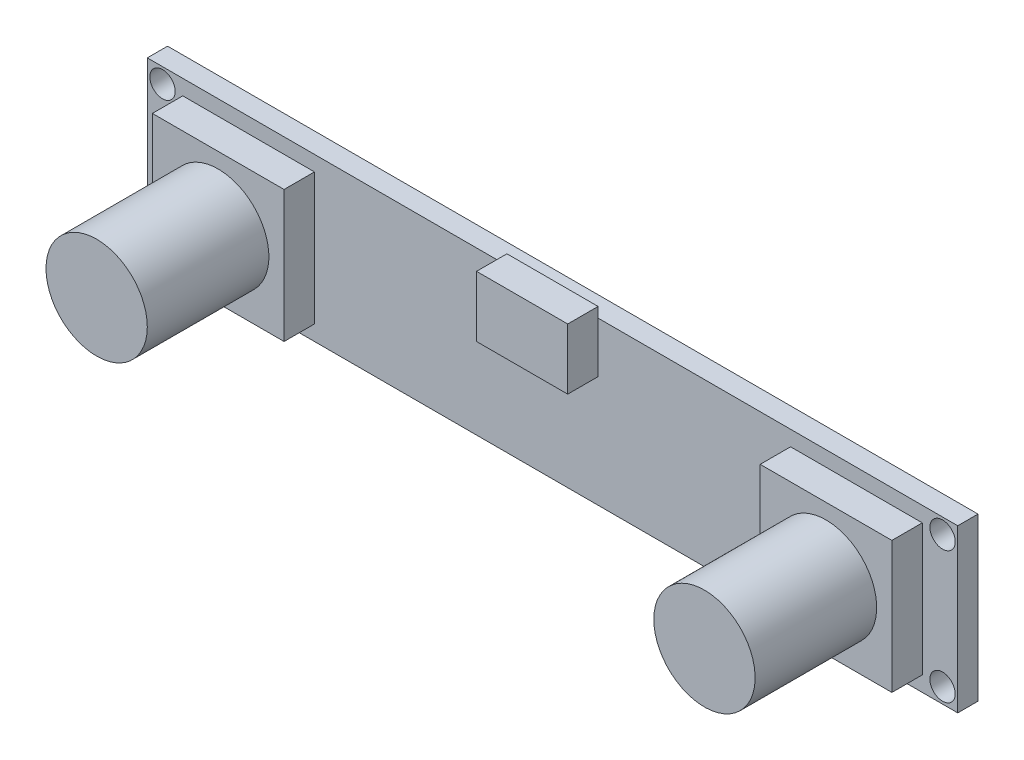
SolidWorks part; units mm, degrees
ref_plane "Спереди" through (0, 0, 0) normal (0, 0, 1) x (1, 0, 0)
ref_plane "Сверху" through (0, 0, 0) normal (0, 1, 0) x (1, 0, 0)
ref_plane "Справа" through (0, 0, 0) normal (1, 0, 0) x (0, 0, -1)
sketch "Эскиз1" plane through (0, 0, 0) normal (0, 0, 1) x (1, 0, 0)
  line L1 (-40, -8) -> (40, -8)
  line L2 (-40, -8) -> (-40, 8)
  line L3 (-40, 8) -> (40, 8)
  line L4 (40, -8) -> (40, 8)
  line L5 (-40, -8) -> (40, 8) construction
  line L6 (-40, 8) -> (40, -8) construction
  point P0 (0, 0)
  dimension "D1" = 80
  dimension "D2" = 16
extrude "тело" add sketch "Эскиз1" along normal blind 2
sketch "Эскиз5" plane through (0, 0, 2) normal (0, 0, 1) x (1, 0, 0)
  line L0 (40, 8) -> (-40, 8) construction
  line L1 (-38.5, -6.5) -> (38.5, -6.5) construction
  line L2 (-38.5, -6.5) -> (-38.5, 6.5) construction
  line L3 (-38.5, 6.5) -> (38.5, 6.5) construction
  line L4 (38.5, -6.5) -> (38.5, 6.5) construction
  line L5 (-38.5, -6.5) -> (38.5, 6.5) construction
  line L6 (-38.5, 6.5) -> (38.5, -6.5) construction
  line L7 (-40, 8) -> (-40, -8) construction
  circle A0 centre (-38.5, 6.5) radius 1.25
  circle A1 centre (38.5, 6.5) radius 1.25
  circle A2 centre (38.5, -6.5) radius 1.25
  circle A3 centre (-38.5, -6.5) radius 1.25
  point P0 (0, 0)
  dimension "D1" = 2.5
  dimension "D2" = 1.5
  dimension "D3" = 1.5
extrude "крепежные отверстия" cut sketch "Эскиз5" against normal through all
sketch "Эскиз3" plane through (0, 0, 2) normal (0, 0, 1) x (1, 0, 0)
  line L0 (-30, 0) -> (30, 0) construction
  line L1 (-36.5, -6.5) -> (-23.5, -6.5)
  line L2 (-36.5, -6.5) -> (-36.5, 6.5)
  line L3 (-36.5, 6.5) -> (-23.5, 6.5)
  line L4 (-23.5, -6.5) -> (-23.5, 6.5)
  line L5 (-36.5, -6.5) -> (-23.5, 6.5) construction
  line L6 (-36.5, 6.5) -> (-23.5, -6.5) construction
  line L7 (23.5, -6.5) -> (36.5, -6.5) construction
  line L8 (23.5, -6.5) -> (23.5, 6.5) construction
  line L9 (23.5, 6.5) -> (36.5, 6.5) construction
  line L10 (36.5, -6.5) -> (36.5, 6.5) construction
  line L11 (23.5, -6.5) -> (36.5, 6.5) construction
  line L12 (23.5, 6.5) -> (36.5, -6.5) construction
  point P0 (-30, 0)
  point P5 (30, 0)
  point P10 (0, 0)
  dimension "D1" = 60
  dimension "D2" = 13
extrude "основание объектива" add sketch "Эскиз3" along normal blind 3
sketch "Эскиз4" plane through (0, 0, 5) normal (0, 0, 1) x (1, 0, 0)
  line L0 (-30, 6.5) -> (-30, -6.5) construction
  line L1 (-23.5, 6.5) -> (-36.5, 6.5) construction
  line L2 (-36.5, -6.5) -> (-23.5, -6.5) construction
  line L4 (-36.5, 6.5) -> (-36.5, -6.5) construction
  line L5 (-36.5, 0) -> (-23.5, 0) construction
  line L6 (-23.5, -6.5) -> (-23.5, 6.5) construction
  circle A0 centre (-30, 0) radius 5
  dimension "D1" = 10
extrude "объектив" add sketch "Эскиз4" along normal blind 12
mirror "Зеркальное отражение1" about plane through (0, 0, 0) normal (1, 0, 0) of "объектив", "основание объектива"
sketch "Эскиз2" plane through (0, 0, 2) normal (0, 0, 1) x (1, 0, 0)
  line L0 (40, 8) -> (-40, 8) construction
  line L1 (-4.5, 9) -> (4.5, 9)
  line L2 (-4.5, 9) -> (-4.5, 3)
  line L3 (-4.5, 3) -> (4.5, 3)
  line L4 (4.5, 9) -> (4.5, 3)
  line L5 (-4.5, 9) -> (4.5, 3) construction
  line L6 (-4.5, 3) -> (4.5, 9) construction
  point P0 (0, 6)
  dimension "D1" = 1
  dimension "D2" = 6
  dimension "D3" = 9
extrude "microusb" add sketch "Эскиз2" along normal blind 3
